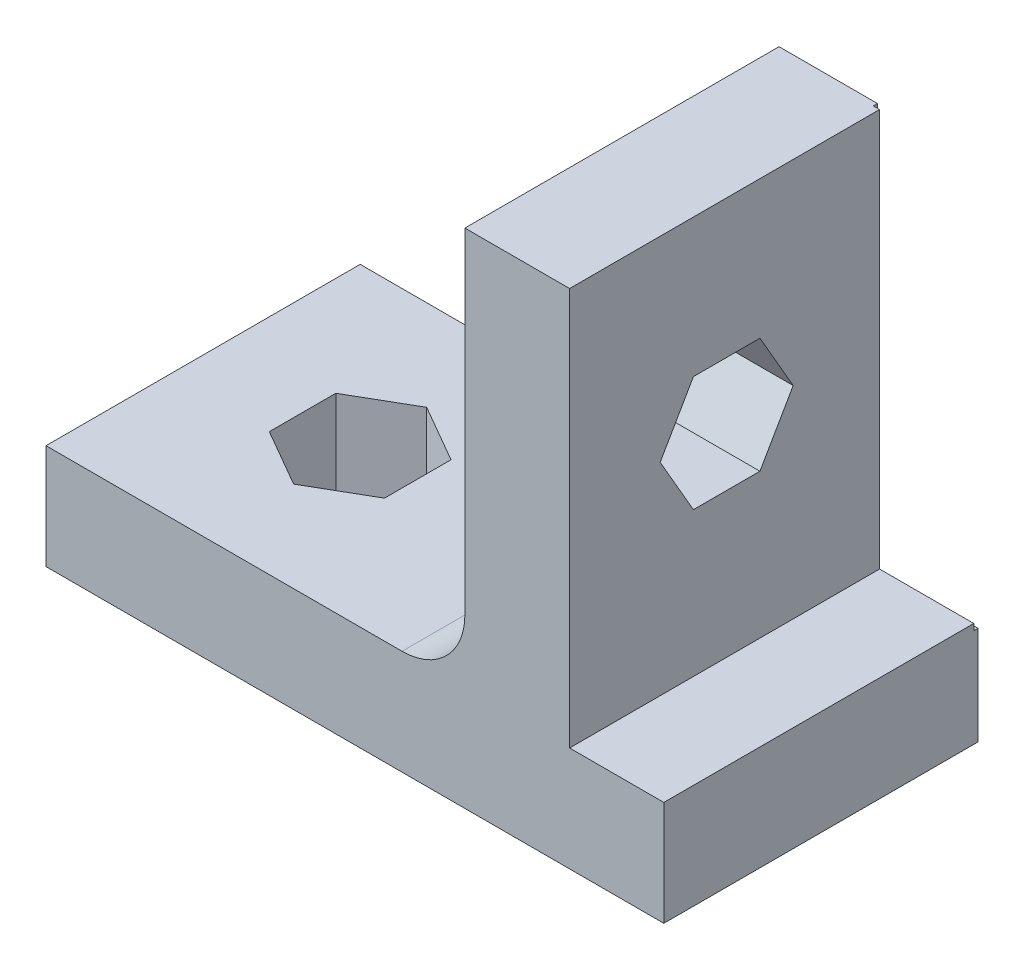
SolidWorks part; units mm, degrees
ref_plane "Front Plane" through (0, 0, 0) normal (0, 0, 1) x (1, 0, 0)
ref_plane "Top Plane" through (0, 0, 0) normal (0, 1, 0) x (1, 0, 0)
ref_plane "Right Plane" through (0, 0, 0) normal (1, 0, 0) x (0, 0, -1)
sketch "Sketch2" plane through (0, 0, 0) normal (0, 0, 1) x (1, 0, 0)
  line L0 (0, 0) -> (29.5, 0)
  line L6 (29.5, 5) -> (25, 5)
  line L7 (25, 5) -> (25, 24)
  line L8 (25, 24) -> (20, 24)
  line L9 (20, 24) -> (20, 5)
  line L10 (20, 5) -> (0, 5)
  line L11 (0, 5) -> (0, 0)
  line L12 (29.5, 0) -> (29.5, 5)
  dimension "D1" = 4.5
  dimension "D2" = 24
  dimension "D3" = 5
  dimension "D4" = 20
  dimension "D5" = 5
extrude "Boss-Extrude1" add sketch "Sketch2" along normal blind 15
sketch "Sketch3" plane through (0, 5, 0) normal (0, 1, 0) x (1, 0, 0)
  line L0 (0, -15) -> (0, 0) construction
  line L1 (27.25, 0) -> (27.25, -15) construction
  line L2 (10.25, -5.9123) -> (7.5, -4.3246)
  line L3 (7.5, -4.3246) -> (4.75, -5.9123)
  line L4 (4.75, -5.9123) -> (4.75, -9.0877)
  line L5 (4.75, -9.0877) -> (7.5, -10.6754)
  line L6 (7.5, -10.6754) -> (10.25, -9.0877)
  line L7 (10.25, -9.0877) -> (10.25, -5.9123)
  line L8 (29.5, 0) -> (25, 0) construction
  line L9 (29.5, -15) -> (25, -15) construction
  line L10 (44.25, -9.0877) -> (44.25, -5.9123)
  line L11 (47, -10.6754) -> (44.25, -9.0877)
  line L12 (49.75, -9.0877) -> (47, -10.6754)
  line L13 (49.75, -5.9123) -> (49.75, -9.0877)
  line L14 (47, -4.3246) -> (49.75, -5.9123)
  line L15 (44.25, -5.9123) -> (47, -4.3246)
  circle A0 centre (7.5, -7.5) radius 2.75 construction
  point P24 (0, 0)
  point P25 (0, -7.5)
  dimension "D1" = 5.5
  dimension "D2" = 7.5
extrude "Cut-Extrude1" cut sketch "Sketch3" against normal through all
sketch "Sketch4" plane through (25, 0, 0) normal (1, 0, 0) x (0, 0, -1)
  line L2 (-15, 24) -> (0, 24) construction
  line L3 (-5.9123, 11.9) -> (-4.3246, 14.65)
  line L4 (-4.3246, 14.65) -> (-5.9123, 17.4)
  line L5 (-5.9123, 17.4) -> (-9.0877, 17.4)
  line L6 (-9.0877, 17.4) -> (-10.6754, 14.65)
  line L7 (-10.6754, 14.65) -> (-9.0877, 11.9)
  line L8 (-9.0877, 11.9) -> (-5.9123, 11.9)
  circle A1 centre (-7.5, 14.65) radius 2.75 construction
  point P3 (0, 0)
  point P4 (-7.5, 24)
  dimension "D1" = 9.35
  dimension "D2" = 5.5
extrude "Cut-Extrude2" cut sketch "Sketch4" against normal through all
sketch "Sketch5" plane through (0, 0, 0) normal (0, 0, -1) x (-1, 0, 0)
  line L4 (-24.7, 23.7) -> (-24.7, 4.7)
  line L5 (-24.7, 4.7) -> (-29.5, 4.7)
  line L12 (0, 0) -> (0, 5)
  line L13 (0, 5) -> (-20, 5)
  line L14 (-20, 5) -> (-20, 24)
  line L15 (-20, 24) -> (-25, 24)
  line L16 (-25, 24) -> (-25, 5)
  line L17 (-25, 5) -> (-29.5, 5)
  line L18 (-29.5, 5) -> (-29.5, 0)
  line L19 (-29.5, 5) -> (-29.5, 0)
  line L23 (-29.5, 0) -> (0, 0)
  line L24 (0, 0) -> (0, 5)
  line L25 (0, 5) -> (-20, 5)
  line L26 (-20, 5) -> (-20, 24)
  line L27 (-20, 24) -> (-25, 24)
  line L28 (-25, 24) -> (-25, 5)
  line L29 (-25, 5) -> (-29.5, 5)
  line L35 (-29.5, 0) -> (0, 0)
  line L36 (-24.7, 23.7) -> (-24.7, 24)
  line L48 (-40.7816, 4.7) -> (-45.8004, 3.989) construction
  line L49 (-45.8004, 3.989) -> (-45.8004, 3.9905) construction
  line L50 (-45.8004, 3.9905) -> (-71.634, 0.3) construction
  line L51 (-29.5, 0.3) -> (-0.3, 0.3) construction
  line L52 (-0.3, 0.3) -> (-0.3, 4.7) construction
  line L53 (-0.3, 4.7) -> (-20.3, 4.7) construction
  line L54 (-20.3, 4.7) -> (-20.3, 23.7) construction
  line L55 (-20.3, 23.7) -> (-24.7, 23.7) construction
  line L58 (-71.634, 0.3) -> (-29.5, 0.3) construction
  line L61 (-29.5, 5) -> (-40.8028, 5) construction
  line L62 (-40.8028, 5) -> (-45.5004, 4.3345) construction
  line L63 (-45.5004, 4.3345) -> (-45.5004, 4.3364) construction
  line L64 (-45.5004, 4.3364) -> (-75.8553, 0) construction
  line L65 (-75.8553, 0) -> (-29.5, 0) construction
  line L66 (-29.5, 4.7) -> (-40.7816, 4.7) construction
  point P24 (0, 0)
  line M29 (-25, 24) -> (-25, 5)
  line M30 (-25, 5) -> (-29.5, 5)
  line M72 (-29.5, 5) -> (-29.5, 0)
  dimension "D1" = 0
  dimension "D2" = 0.3
extrude "Cut-Extrude4" cut sketch "Sketch5" against normal blind 0.2 contours L4 L36 L27 L5 M29 M30 M72
fillet "Fillet1" radius 3 1 edges at (20, 5, 7.5)
